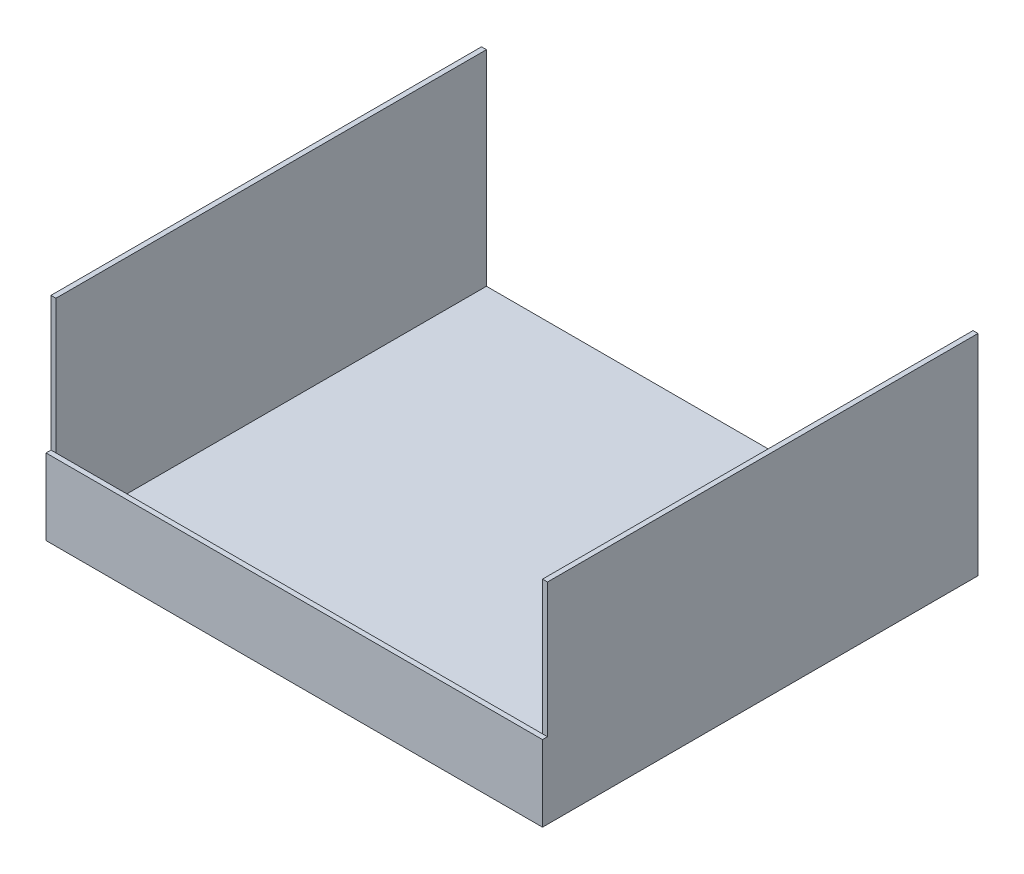
SolidWorks part; units mm, degrees
ref_plane "Front Plane" through (0, 0, 0) normal (0, 0, 1) x (1, 0, 0)
ref_plane "Top Plane" through (0, 0, 0) normal (0, 1, 0) x (1, 0, 0)
ref_plane "Right Plane" through (0, 0, 0) normal (1, 0, 0) x (0, 0, -1)
sketch "Sketch2" plane through (0, 0, 0) normal (0, 1, 0) x (1, 0, 0)
  line L1 (-111.3245, 133.7328) -> (88.7005, 133.7328)
  line L2 (-111.3245, 133.7328) -> (-111.3245, -41.7172)
  line L3 (-111.3245, -41.7172) -> (88.7005, -41.7172)
  line L4 (88.7005, 133.7328) -> (88.7005, -41.7172)
  dimension "D1" = 175.45
  dimension "D2" = 200.025
extrude "Boss-Extrude1" add sketch "Sketch2" along normal blind 2
sketch "Sketch3" plane through (0, 2, 0) normal (0, 1, 0) x (1, 0, 0)
  line L5 (-111.3245, -41.7172) -> (88.7005, -41.7172) construction
  line L10 (-111.3245, 133.7328) -> (-109.3245, 133.7328)
  line L11 (-111.3245, 133.7328) -> (-111.3245, -39.7172)
  line L12 (-111.3245, -39.7172) -> (-109.3245, -39.7172)
  line L13 (-109.3245, 133.7328) -> (-109.3245, -39.7172)
  line L15 (88.7005, 133.7328) -> (86.7005, 133.7328)
  line L16 (88.7005, 133.7328) -> (88.7005, -39.7172)
  line L17 (88.7005, -39.7172) -> (86.7005, -39.7172)
  line L18 (86.7005, 133.7328) -> (86.7005, -39.7172)
  dimension "D1" = 2
  dimension "D2" = 2
  dimension "D3" = 2
extrude "Boss-Extrude2" add sketch "Sketch3" along normal blind 82.55
sketch "Sketch4" plane through (0, 2, 0) normal (0, 1, 0) x (1, 0, 0)
  line L7 (-111.3245, -39.7172) -> (88.7005, -39.7172)
  line L8 (-111.3245, -39.7172) -> (-111.3245, -41.7172)
  line L9 (-111.3245, -41.7172) -> (88.7005, -41.7172)
  line L10 (88.7005, -39.7172) -> (88.7005, -41.7172)
extrude "Boss-Extrude4" add sketch "Sketch4" along normal blind 28.575 contours L7 L10 L9 L8
